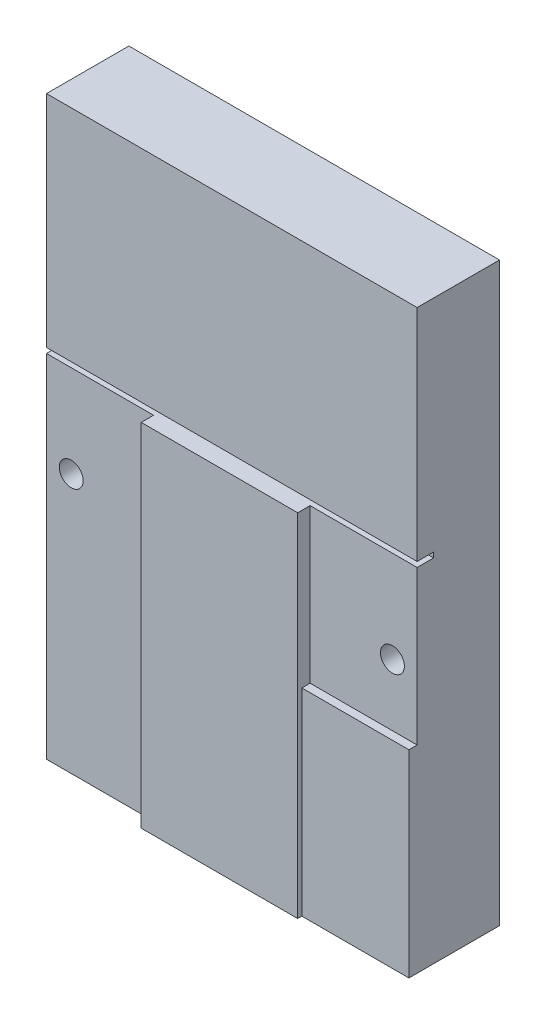
SolidWorks part; units mm, degrees
ref_plane "Front Plane" through (0, 0, 0) normal (0, 0, 1) x (1, 0, 0)
ref_plane "Top Plane" through (0, 0, 0) normal (0, 1, 0) x (1, 0, 0)
ref_plane "Right Plane" through (0, 0, 0) normal (1, 0, 0) x (0, 0, -1)
sketch "Sketch2" plane through (0, 0, 0) normal (0, 1, 0) x (1, 0, 0)
  line L1 (22.5, 5) -> (-22.5, 5)
  line L2 (22.5, 5) -> (22.5, -5)
  line L3 (22.5, -5) -> (-22.5, -5)
  line L4 (-22.5, 5) -> (-22.5, -5)
  line L5 (22.5, 5) -> (-22.5, -5) construction
  line L6 (22.5, -5) -> (-22.5, 5) construction
  point P0 (0, 0)
  dimension "D1" = 10
  dimension "D2" = 45
extrude "Boss-Extrude1" add sketch "Sketch2" along normal blind 40
sketch "Sketch3" plane through (0, 0, -5) normal (0, 0, -1) x (-1, 0, 0)
  line L0 (0, 0) -> (0, 40) construction
  line L1 (-22.5, 40) -> (22.5, 40) construction
  line L3 (22.5, 40) -> (22.5, 0) construction
  line L4 (-22.5, 40) -> (-22.5, 0) construction
  line L5 (-22.5, 0) -> (22.5, 0) construction
  line L6 (-22.5, 11.5) -> (22.5, 11.5) construction
  circle A0 centre (19.5, 2.25) radius 1.45
  circle A3 centre (-19.5, 2.25) radius 1.45
  circle A4 centre (-19.5, 20.75) radius 1.45
  circle A5 centre (19.5, 20.75) radius 1.45
  dimension "D3" = 2.9
  dimension "D4" = 3
  dimension "D1" = 3
  dimension "D2" = 2.25
sketch "Sketch4" plane through (0, 40, 0) normal (0, 1, 0) x (1, 0, 0)
  line L1 (-22.5, 5) -> (22.5, 5)
  line L2 (-22.5, 5) -> (-22.5, -5)
  line L3 (-22.5, -5) -> (22.5, -5)
  line L4 (22.5, 5) -> (22.5, -5)
extrude "Boss-Extrude2" add sketch "Sketch4" along normal blind 10
sketch "Sketch6" plane through (0, 0, -5) normal (0, 0, -1) x (-1, 0, 0)
  line L2 (-22.5, 23) -> (22.7712, 23) construction
  circle A1 centre (-19.5, 20.75) radius 1.45 construction
  dimension "D1" = 2.25
sketch "Sketch8" plane through (0, 0, 0) normal (0, -1, 0) x (1, 0, 0)
  line L1 (-22.5, 5) -> (22.5, 5)
  line L2 (-22.5, 5) -> (-22.5, -5)
  line L3 (-22.5, -5) -> (22.5, -5)
  line L4 (22.5, 5) -> (22.5, -5)
extrude "Boss-Extrude3" add sketch "Sketch8" along normal blind 20
sketch "Sketch9" plane through (0, 0, 5) normal (0, 0, 1) x (1, 0, 0)
  line L0 (22.5, 11.5) -> (-22.5, 11.5) construction
  line L1 (-22.5, 50) -> (-22.5, -20) construction
  line L2 (22.5, 50) -> (22.5, -20) construction
  circle A0 centre (19.5, 20.75) radius 1.45 construction
  circle A1 centre (19.5, 2.25) radius 1.45 construction
  circle A2 centre (19.5, 11.5) radius 1.45
  circle A3 centre (-19.5, 11.5) radius 1.45
  dimension "D1" = 18.5
  dimension "D2" = 3
  dimension "D3" = 3
  dimension "D4" = 3
extrude "Cut-Extrude2" cut sketch "Sketch9" against normal blind 20
sketch "Sketch10" plane through (0, 0, 5) normal (0, 0, 1) x (1, 0, 0)
  line L1 (-22.5, 50) -> (-22.5, -20) construction
  line L2 (-22.5, 23.2975) -> (22.5, 23.2975)
  line L3 (-22.5, 23.2975) -> (-22.5, 22.6713)
  line L4 (-22.5, 22.6713) -> (22.5, 22.6713)
  line L5 (22.5, 23.2975) -> (22.5, 22.6713)
  line L6 (22.5, 50) -> (22.5, -20) construction
extrude "Cut-Extrude3" cut sketch "Sketch10" against normal blind 2
sketch "Sketch11" plane through (0, 0, 5) normal (0, 0, 1) x (1, 0, 0)
  line L0 (-22.5, 22.6713) -> (22.5, 22.6713) construction
  line L1 (-9.5, 22.6713) -> (9.5, 22.6713)
  line L2 (-9.5, 22.6713) -> (-9.5, -20)
  line L3 (-9.5, -20) -> (9.5, -20)
  line L4 (9.5, 22.6713) -> (9.5, -20)
  line L5 (22.5, -20) -> (-22.5, -20) construction
  line L6 (22.5, 22.6713) -> (22.5, -20) construction
  line L8 (-22.5, 22.6713) -> (-22.5, -20) construction
  dimension "D1" = 19
  dimension "D2" = 13
  dimension "D3" = 13
extrude "Boss-Extrude4" add sketch "Sketch11" along normal blind 1.5
sketch "Sketch12" plane through (0, 0, 5) normal (0, 0, 1) x (1, 0, 0)
  line L0 (22.5, 4) -> (9.5, 4) construction
  line L1 (22.5, 22.6713) -> (22.5, -20) construction
  line L2 (9.5, -20) -> (9.5, 22.6713) construction
  line L3 (22.5, 23) -> (-22.7712, 23) construction
  line M3 (9.5, 22.6713) -> (9.5, -20)
  line M4 (9.5, -20) -> (22.5, -20)
  line M5 (22.5, -20) -> (22.5, 22.6713)
  dimension "D1" = 19
extrude "Boss-Extrude5" add sketch "Sketch12" along normal blind 1 contours L0 M5 M3 M4
